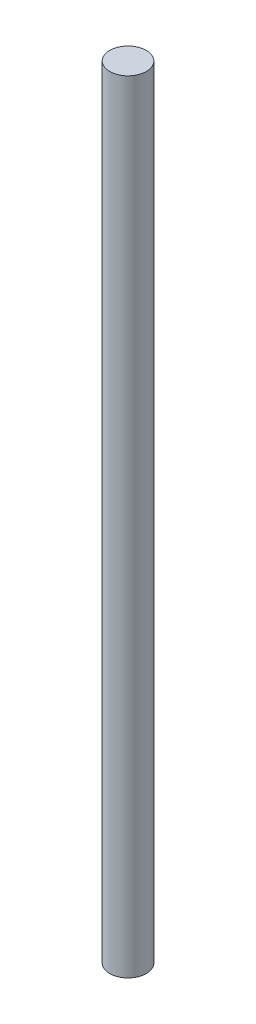
SolidWorks part; units mm, degrees
material "Nylon 101"
ref_plane "Alzado" through (0, 0, 0) normal (0, 0, 1) x (1, 0, 0)
ref_plane "Planta" through (0, 0, 0) normal (0, 1, 0) x (1, 0, 0)
ref_plane "Vista lateral" through (0, 0, 0) normal (1, 0, 0) x (0, 0, -1)
sketch "Sketch1" plane through (0, 0, 0) normal (0, 0, 1) x (1, 0, 0)
  line L0 (0, 0) -> (1.1, 0)
  line L1 (1.1, 0) -> (1.1, -47)
  line L2 (1.1, -47) -> (0, -47)
  line L3 (0, -47) -> (0, 0)
  line L4 (0, -51) -> (0, 4) construction
revolve "Tendon" add sketch "Sketch1" angle 360 about L4
